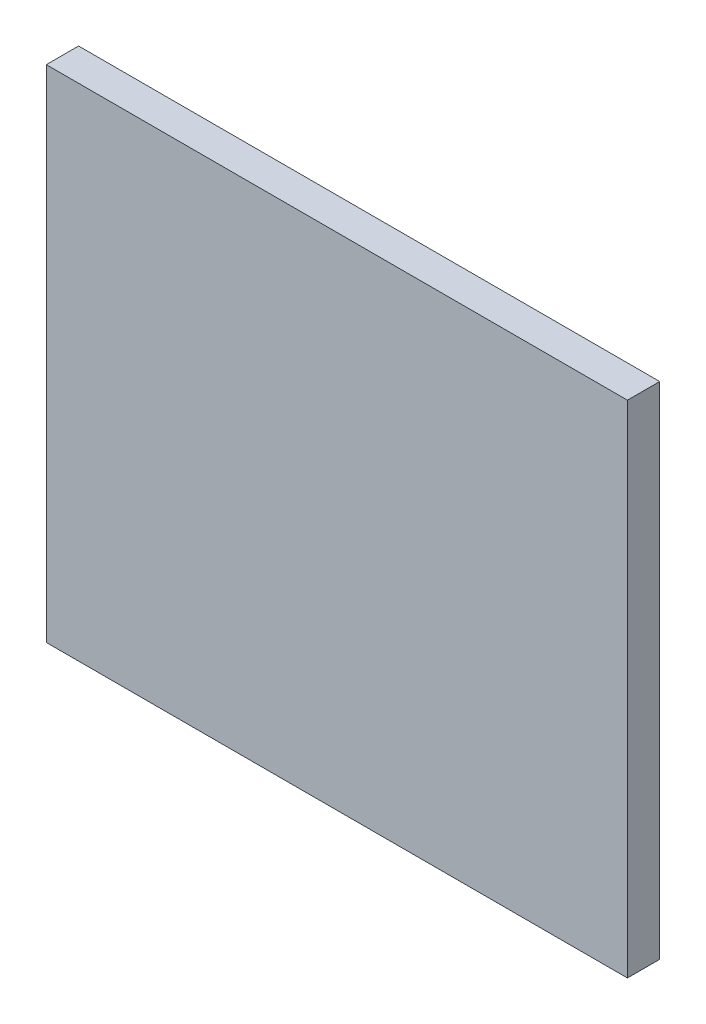
SolidWorks part; units mm, degrees
ref_plane "Front Plane" through (0, 0, 0) normal (0, 0, 1) x (1, 0, 0)
ref_plane "Top Plane" through (0, 0, 0) normal (0, 1, 0) x (1, 0, 0)
ref_plane "Right Plane" through (0, 0, 0) normal (1, 0, 0) x (0, 0, -1)
sketch "Sketch1" plane through (0, 0, 0) normal (0, 0, 1) x (1, 0, 0)
  line L1 (0, 0) -> (36, 0)
  line L2 (0, 0) -> (0, 31)
  line L3 (0, 31) -> (36, 31)
  line L4 (36, 0) -> (36, 31)
  dimension "D1" = 36
  dimension "D2" = 31
extrude "Profile" add sketch "Sketch1" along normal blind 2
equation "\"Profile_Depth\"= 2mm"
equation "\"D1@Profile\" = \"Profile_Depth\""
equation "\"Profile_Sketch_1\"= 36mm"
equation "\"D1@Sketch1\" = \"Profile_Sketch_1\""
equation "\"Profile_Sketch_2\"= 31mm"
equation "\"D2@Sketch1\" = \"Profile_Sketch_2\""
equation "\"EnvelopeWidth\"= 36mm"
equation "\"EnvelopeHeight\"= 31mm"
